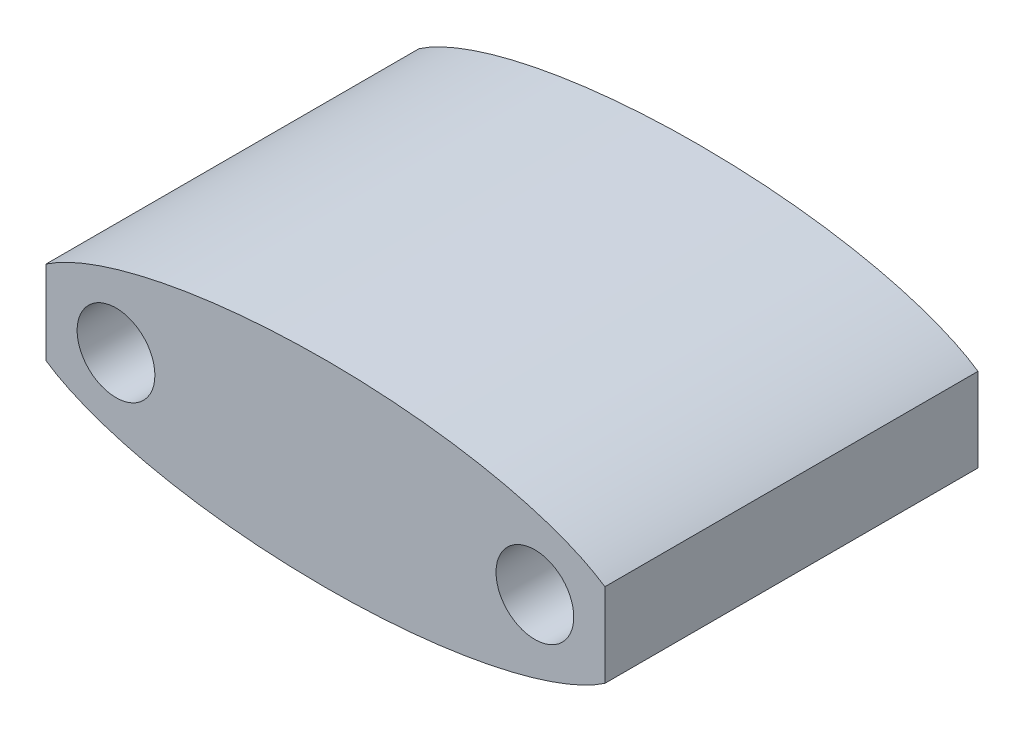
SolidWorks part; units mm, degrees
ref_plane "Front Plane" through (0, 0, 0) normal (0, 0, 1) x (1, 0, 0)
ref_plane "Top Plane" through (0, 0, 0) normal (0, 1, 0) x (1, 0, 0)
ref_plane "Right Plane" through (0, 0, 0) normal (1, 0, 0) x (0, 0, -1)
sketch "Sketch1" plane through (0, 0, 0) normal (0, 0, 1) x (1, 0, 0)
  line L0 (-89.8766, -13.46) -> (-89.8766, 13.46)
  line L2 (89.8766, -13.46) -> (89.8766, 13.46)
  ellipse E0 centre (0, 0) end of major axis (-99.2732, 0) minor radius 31.6948 (-89.8766, -13.46) -> (89.8766, -13.46) ccw
  ellipse E1 centre (0, 0) end of major axis (-99.2732, 0) minor radius 31.6948 (89.8766, 13.46) -> (-89.8766, 13.46) ccw
extrude "Boss-Extrude1" add sketch "Sketch1" along normal blind 120
sketch "Sketch2" plane through (0, 0, 120) normal (0, 0, 1) x (1, 0, 0)
  line L0 (0, 31.6948) -> (0, -31.6948) construction
  circle A0 centre (-67.3584, 0) radius 12.5
  circle A1 centre (67.3584, 0) radius 12.5
  ellipse E0 centre (0, 0) end of major axis (-99.2732, 0) minor radius 31.6948 (89.8766, 13.46) -> (-89.8766, 13.46) ccw construction
  ellipse E1 centre (0, 0) end of major axis (-99.2732, 0) minor radius 31.6948 (-89.8766, -13.46) -> (89.8766, -13.46) ccw construction
  dimension "D1" = 25
extrude "Cut-Extrude1" cut sketch "Sketch2" against normal blind 80
